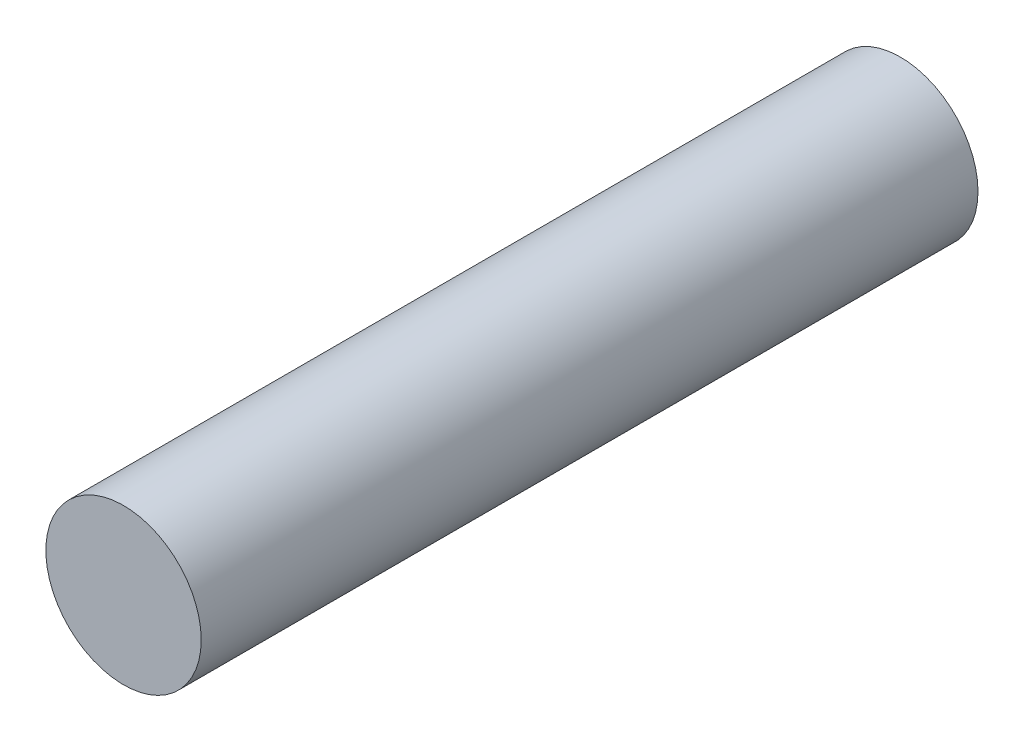
SolidWorks part; units mm, degrees
ref_plane "Front Plane" through (0, 0, 0) normal (0, 0, 1) x (1, 0, 0)
ref_plane "Top Plane" through (0, 0, 0) normal (0, 1, 0) x (1, 0, 0)
ref_plane "Right Plane" through (0, 0, 0) normal (1, 0, 0) x (0, 0, -1)
sketch "Sketch1" plane through (0, 0, 0) normal (0, 0, 1) x (1, 0, 0)
  circle A0 centre (0, 0) radius 15
  dimension "D1" = 30
extrude "Boss-Extrude1" add sketch "Sketch1" along normal blind 150
